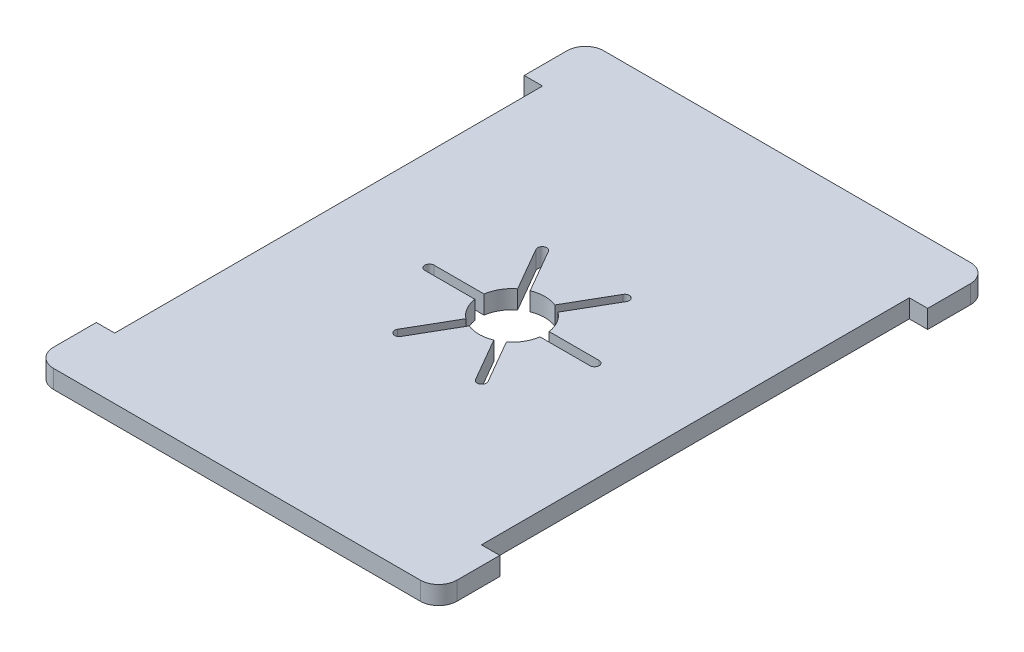
SolidWorks part; units mm, degrees
ref_plane "Front Plane" through (0, 0, 0) normal (0, 0, 1) x (1, 0, 0)
ref_plane "Top Plane" through (0, 0, 0) normal (0, 1, 0) x (1, 0, 0)
ref_plane "Right Plane" through (0, 0, 0) normal (1, 0, 0) x (0, 0, -1)
sketch "Sketch1" plane through (0, 0, 0) normal (0, 1, 0) x (1, 0, 0)
  line L0 (0, 0) -> (0, 34.8107) construction
  line L1 (-30, -45) -> (30, -45)
  line L2 (-33, -42) -> (-33, 42)
  line L3 (-30, 45) -> (30, 45)
  line L4 (33, -42) -> (33, 42)
  line L5 (-33, -45) -> (33, 45) construction
  line L6 (-33, 45) -> (33, -45) construction
  line L7 (-33, 35) -> (-30, 35)
  line L8 (-33, 35) -> (-33, -35)
  line L9 (-33, -35) -> (-30, -35)
  line L10 (-30, 35) -> (-30, -35)
  line L11 (30, 35) -> (30, -35)
  line L12 (33, -35) -> (30, -35)
  line L13 (33, 35) -> (33, -35)
  line L14 (33, 35) -> (30, 35)
  arc A0 (-30, -45) -> (-33, -42) centre (-30, -42) cw
  arc A1 (30, -45) -> (33, -42) centre (30, -42) ccw
  arc A2 (30, 45) -> (33, 42) centre (30, 42) cw
  arc A3 (-33, 42) -> (-30, 45) centre (-30, 42) cw
  point P0 (0, 0)
  point P12 (-30, 0)
  dimension "D5" = 3
  dimension "D1" = 90
  dimension "D2" = 66
  dimension "D3" = 3
  dimension "D4" = 70
extrude "Boss-Extrude1" add sketch "Sketch1" along normal blind 3 contours A3 L2 L7 L10 L9 A0 L1 A1 L4 L12 L11 L14 A2 L3
sketch "Sketch2" plane through (0, 3, 0) normal (0, 1, 0) x (1, 0, 0)
  line L0 (-32.1213, 44.1213) -> (32.1213, -44.1213) construction
  line L1 (32.1213, -44.1213) -> (33, 45) construction
  line L2 (33, 45) -> (-32.1724, -45) construction
  line L3 (-13.5, 0) -> (13.5, 0) construction
  line L4 (-13.5, 0.75) -> (13.5, 0.75)
  line L5 (-13.5, -0.75) -> (13.5, -0.75)
  line L6 (-6.75, -11.6913) -> (6.75, 11.6913) construction
  line L7 (-7.3995, -11.3163) -> (6.1005, 12.0663)
  line L8 (-6.1005, -12.0663) -> (7.3995, 11.3163)
  line L9 (6.75, -11.6913) -> (-6.75, 11.6913) construction
  line L10 (6.1005, -12.0663) -> (-7.3995, 11.3163)
  line L11 (7.3995, -11.3163) -> (-6.1005, 12.0663)
  line L12 (13.5, 0) -> (-13.5, 0) construction
  line L13 (13.5, -0.75) -> (-13.5, -0.75)
  line L14 (13.5, 0.75) -> (-13.5, 0.75)
  line L15 (6.75, 11.6913) -> (-6.75, -11.6913) construction
  line L16 (7.3995, 11.3163) -> (-6.1005, -12.0663)
  line L17 (6.1005, 12.0663) -> (-7.3995, -11.3163)
  line L18 (-6.75, 11.6913) -> (6.75, -11.6913) construction
  line L19 (-6.1005, 12.0663) -> (7.3995, -11.3163)
  line L20 (-7.3995, 11.3163) -> (6.1005, -12.0663)
  arc A0 (-30, 45) -> (-33, 42) centre (-30, 42) ccw construction
  arc A1 (30, -45) -> (33, -42) centre (30, -42) ccw construction
  circle A2 centre (0, 0) radius 2.69
  arc A3 (-13.5, 0.75) -> (-13.5, -0.75) centre (-13.5, 0) ccw
  arc A4 (13.5, -0.75) -> (13.5, 0.75) centre (13.5, 0) ccw
  circle A5 centre (0, 0) radius 2.69
  arc A6 (-7.3995, -11.3163) -> (-6.1005, -12.0663) centre (-6.75, -11.6913) ccw
  arc A7 (7.3995, 11.3163) -> (6.1005, 12.0663) centre (6.75, 11.6913) ccw
  circle A8 centre (0, 0) radius 2.69
  arc A9 (6.1005, -12.0663) -> (7.3995, -11.3163) centre (6.75, -11.6913) ccw
  arc A10 (-6.1005, 12.0663) -> (-7.3995, 11.3163) centre (-6.75, 11.6913) ccw
  circle A11 centre (0, 0) radius 2.69
  arc A12 (13.5, -0.75) -> (13.5, 0.75) centre (13.5, 0) ccw
  arc A13 (-13.5, 0.75) -> (-13.5, -0.75) centre (-13.5, 0) ccw
  circle A14 centre (0, 0) radius 2.69
  arc A15 (7.3995, 11.3163) -> (6.1005, 12.0663) centre (6.75, 11.6913) ccw
  arc A16 (-7.3995, -11.3163) -> (-6.1005, -12.0663) centre (-6.75, -11.6913) ccw
  circle A17 centre (0, 0) radius 2.69
  arc A18 (-6.1005, 12.0663) -> (-7.3995, 11.3163) centre (-6.75, 11.6913) ccw
  arc A19 (6.1005, -12.0663) -> (7.3995, -11.3163) centre (6.75, -11.6913) ccw
  point P15 (0, 0)
  point P25 (0, 0)
  point P33 (0, 0)
  point P41 (0, 0)
  point P49 (0, 0)
  point P57 (0, 0)
  point P62 (0, 0)
  dimension "D1" = 5.38
  dimension "D2" = 0.75
  dimension "D3" = 27
  dimension "D4" = 6
extrude "Cut-Extrude1" cut sketch "Sketch2" against normal blind 10 contours L13 A2 L17 | L16 A2 L20 | L19 A2 L5 | L4 A2 L8 | L7 A2 L11 | L10 A2 L14
sketch "Sketch3" plane through (0, 3, 0) normal (0, 1, 0) x (1, 0, 0)
  circle A0 centre (0, 0) radius 5.375
  dimension "D1" = 10.75
extrude "Cut-Extrude2" cut sketch "Sketch3" against normal blind 10
